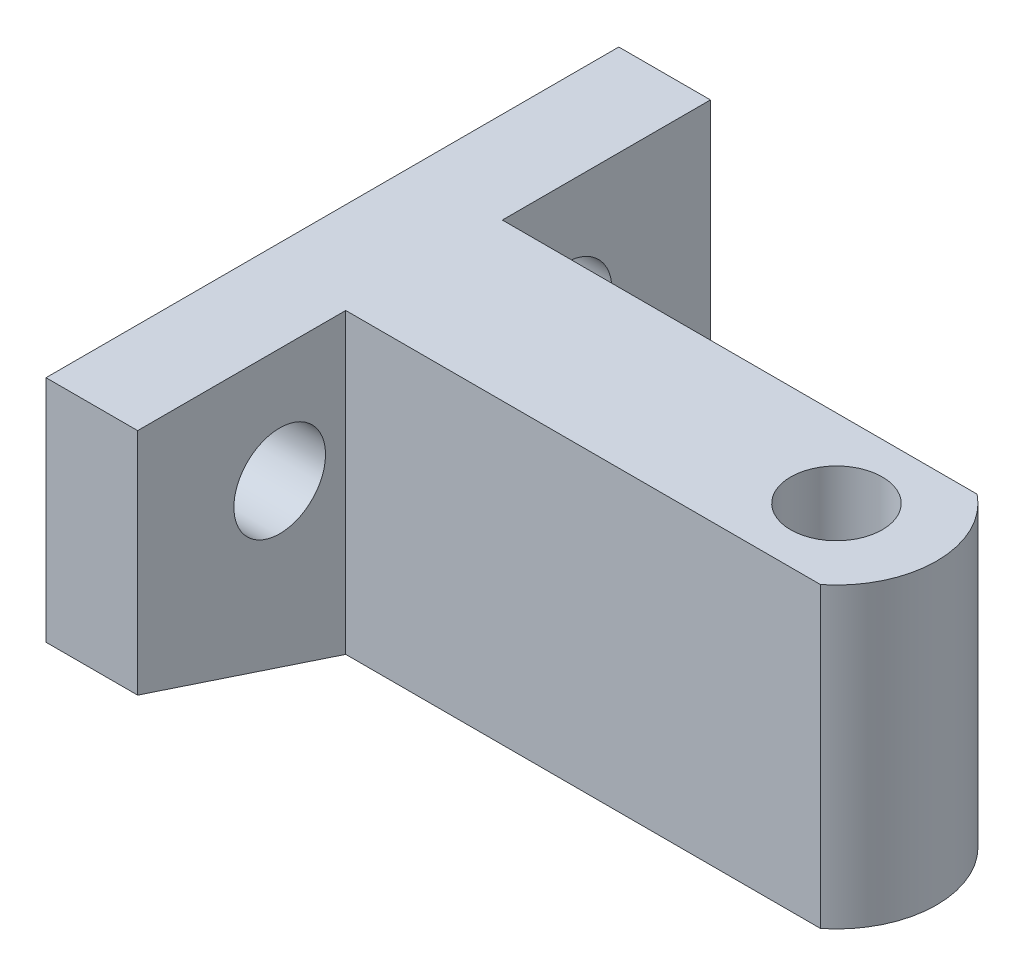
SolidWorks part; units mm, degrees
ref_plane "Alzado" through (0, 0, 0) normal (0, 0, 1) x (1, 0, 0)
ref_plane "Planta" through (0, 0, 0) normal (0, 1, 0) x (1, 0, 0)
ref_plane "Vista lateral" through (0, 0, 0) normal (1, 0, 0) x (0, 0, -1)
sketch "Croquis1" plane through (0, 0, 0) normal (1, 0, 0) x (0, 0, -1)
  line L1 (-5.141, 0.1273) -> (19.859, 0.1273)
  line L2 (-5.141, 0.1273) -> (-5.141, 10.1273)
  line L3 (-5.141, 10.1273) -> (19.859, 10.1273)
  line L4 (19.859, 0.1273) -> (19.859, 10.1273)
  circle A0 centre (1.059, 5.1273) radius 2
  circle A1 centre (13.559, 5.1273) radius 2
  dimension "D3" = 4
  dimension "D4" = 4
  dimension "D1" = 25
  dimension "D2" = 10
  dimension "D5" = 5
  dimension "D6" = 12.5
  dimension "D7" = 6.3
extrude "Saliente-Extruir1" add sketch "Croquis1" along normal blind 4
sketch "Croquis2" plane through (4, 0, 0) normal (1, 0, 0) x (0, 0, -1)
  line L1 (3.9414, -2.8727) -> (10.7765, -2.8727)
  line L2 (3.9414, -2.8727) -> (3.9414, 10.1273)
  line L3 (3.9414, 10.1273) -> (10.7765, 10.1273)
  line L4 (10.7765, -2.8727) -> (10.7765, 10.1273)
  line L5 (3.9414, -2.8727) -> (10.7765, 10.1273) construction
  line L6 (3.9414, 10.1273) -> (10.7765, -2.8727) construction
  point P0 (7.359, 3.6273)
  dimension "D1" = 13
extrude "Saliente-Extruir2" add sketch "Croquis2" along normal blind 24
sketch "Croquis3" plane through (0, 10.1273, 0) normal (0, 1, 0) x (1, 0, 0)
  line L0 (28, 10.7765) -> (28, 3.9414) construction
  circle A0 centre (22, 7.359) radius 2
  dimension "D1" = 4
  dimension "D2" = 6
extrude "Cortar-Extruir1" cut sketch "Croquis3" against normal blind 24
sketch "Croquis4" plane through (4, 0, 0) normal (1, 0, 0) x (0, 0, -1)
  line L0 (-5.141, 0.1273) -> (3.9414, -2.8727)
  line L1 (3.9414, -2.8727) -> (10.7765, -2.8727) construction
  line L2 (3.9414, 10.1273) -> (3.9414, -2.8727) construction
  line L3 (3.9414, -2.8727) -> (10.7765, -2.8727)
  line L4 (10.7765, -2.8727) -> (19.859, 0.1273)
  line L5 (19.859, 0.1273) -> (-5.141, 0.1273)
extrude "Saliente-Extruir3" add sketch "Croquis4" against normal through all
sketch "Croquis5" plane through (0, 10.1273, 0) normal (0, 1, 0) x (1, 0, 0)
  line L9 (28, 3.9414) -> (24.7207, 3.9414)
  line L10 (28, 3.9414) -> (4, 3.9414) construction
  line L11 (28, 3.9414) -> (28, 10.7765)
  line L12 (28, 10.7765) -> (24.7207, 10.7765)
  line L13 (28, 10.7765) -> (4, 10.7765) construction
  arc A2 (24.7207, 3.9414) -> (24.7207, 10.7765) centre (22, 7.359) ccw
  point P8 (28, 3.9414)
extrude "Cortar-Extruir2" cut sketch "Croquis5" against normal blind 24
